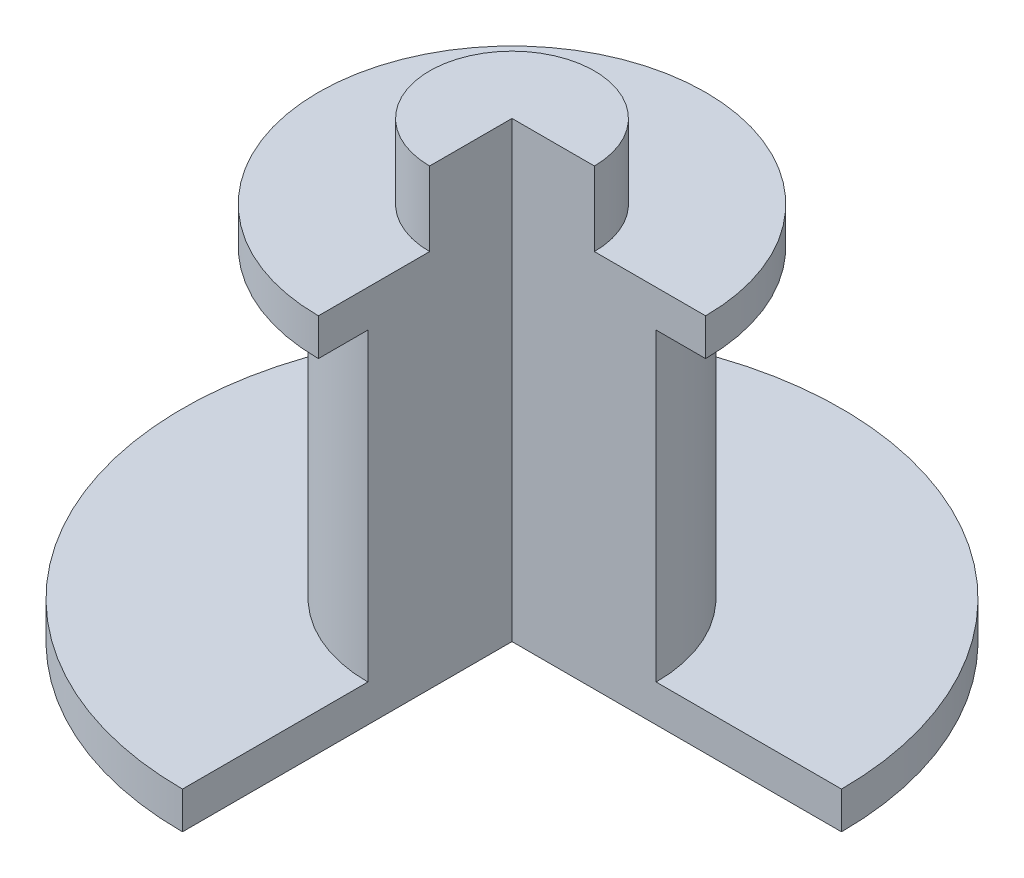
SolidWorks part; units mm, degrees
material "Cast Alloy Steel"
ref_plane "Front Plane" through (0, 0, 0) normal (0, 0, 1) x (1, 0, 0)
ref_plane "Top Plane" through (0, 0, 0) normal (0, 1, 0) x (1, 0, 0)
ref_plane "Right Plane" through (0, 0, 0) normal (1, 0, 0) x (0, 0, -1)
sketch "Sketch1" plane through (0, 0, 0) normal (0, 0, 1) x (1, 0, 0)
  line L0 (0, 0) -> (0, 71415.7091) construction
  line L1 (0, 0) -> (-80, 0)
  line L2 (-80, 0) -> (-80, 9)
  line L3 (-80, 9) -> (-35, 9)
  line L4 (-35, 9) -> (-35, 83)
  line L5 (-35, 83) -> (-47, 83)
  line L6 (-47, 83) -> (-47, 92)
  line L7 (-47, 92) -> (-20, 92)
  line L8 (-20, 92) -> (-20, 110)
  line L9 (-20, 110) -> (0, 110)
  line L10 (0, 110) -> (0, 0)
  dimension "D1" = 160
  dimension "D2" = 70
  dimension "D3" = 9
  dimension "D4" = 74
  dimension "D5" = 9
  dimension "D6" = 94
  dimension "D7" = 40
  dimension "D8" = 110
revolve "Revolve1" add sketch "Sketch1" angle 180 about L0
